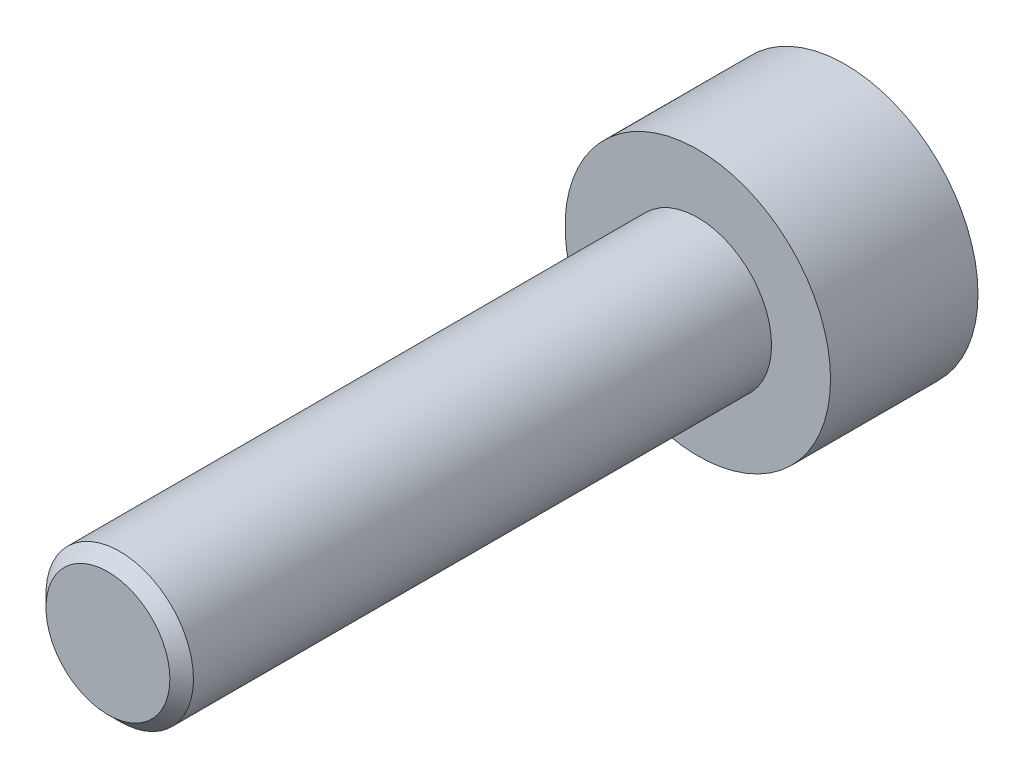
SolidWorks part; units mm, degrees
material "AISI 304"
ref_plane "前视基准面" through (0, 0, 0) normal (0, 0, 1) x (1, 0, 0)
ref_plane "上视基准面" through (0, 0, 0) normal (0, 1, 0) x (1, 0, 0)
ref_plane "右视基准面" through (0, 0, 0) normal (1, 0, 0) x (0, 0, -1)
sketch "草图1" plane through (0, 0, 0) normal (0, 0, 1) x (1, 0, 0)
  circle A0 centre (0, 0) radius 2.25
  dimension "D1" = 4.5
extrude "凸台-拉伸1" add sketch "草图1" along normal blind 2.5
sketch "草图2" plane through (0, 0, 2.5) normal (0, 0, 1) x (1, 0, 0)
  circle A0 centre (0, 0) radius 1.25
  dimension "D1" = 2.5
extrude "凸台-拉伸2" add sketch "草图2" along normal blind 10
chamfer "倒角1" distance 0.2 angle 45 1 edges at (1.25, 0, 12.5)
sketch "草图3" plane through (0, 0, 0) normal (0, 0, -1) x (-1, 0, 0)
  line L0 (0, 1.1778) -> (-1.02, 0.5889)
  line L1 (-1.02, 0.5889) -> (-1.02, -0.5889)
  line L2 (-1.02, -0.5889) -> (0, -1.1778)
  line L3 (0, -1.1778) -> (1.02, -0.5889)
  line L4 (1.02, -0.5889) -> (1.02, 0.5889)
  line L5 (1.02, 0.5889) -> (0, 1.1778)
  dimension "D1" = 2.04
extrude "切除-拉伸1" cut sketch "草图3" against normal blind 1.1
